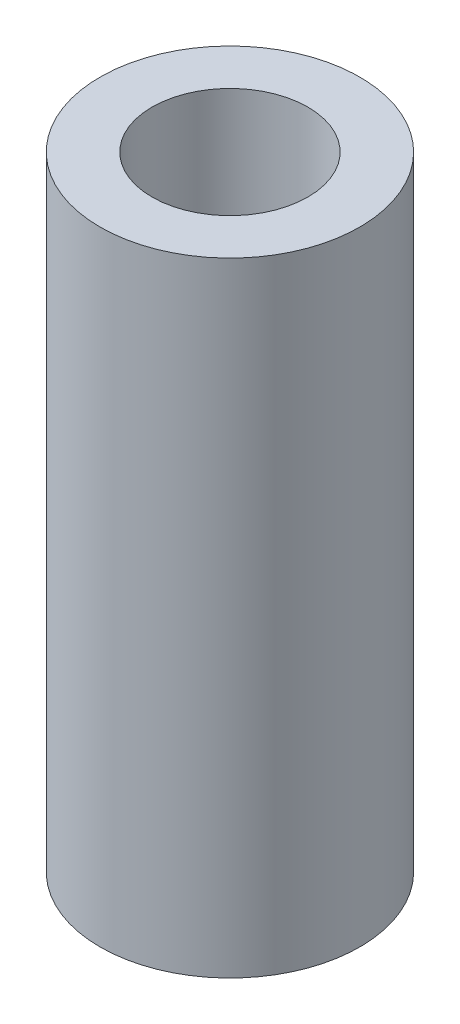
SolidWorks part; units mm, degrees
ref_plane "Front Plane" through (0, 0, 0) normal (0, 0, 1) x (1, 0, 0)
ref_plane "Top Plane" through (0, 0, 0) normal (0, 1, 0) x (1, 0, 0)
ref_plane "Right Plane" through (0, 0, 0) normal (1, 0, 0) x (0, 0, -1)
sketch "Sketch1" plane through (0, 0, 0) normal (0, 1, 0) x (1, 0, 0)
  circle A0 centre (0, 0) radius 25
  circle A1 centre (0, 0) radius 15
extrude "Boss-Extrude1" add sketch "Sketch1" along normal blind 120
